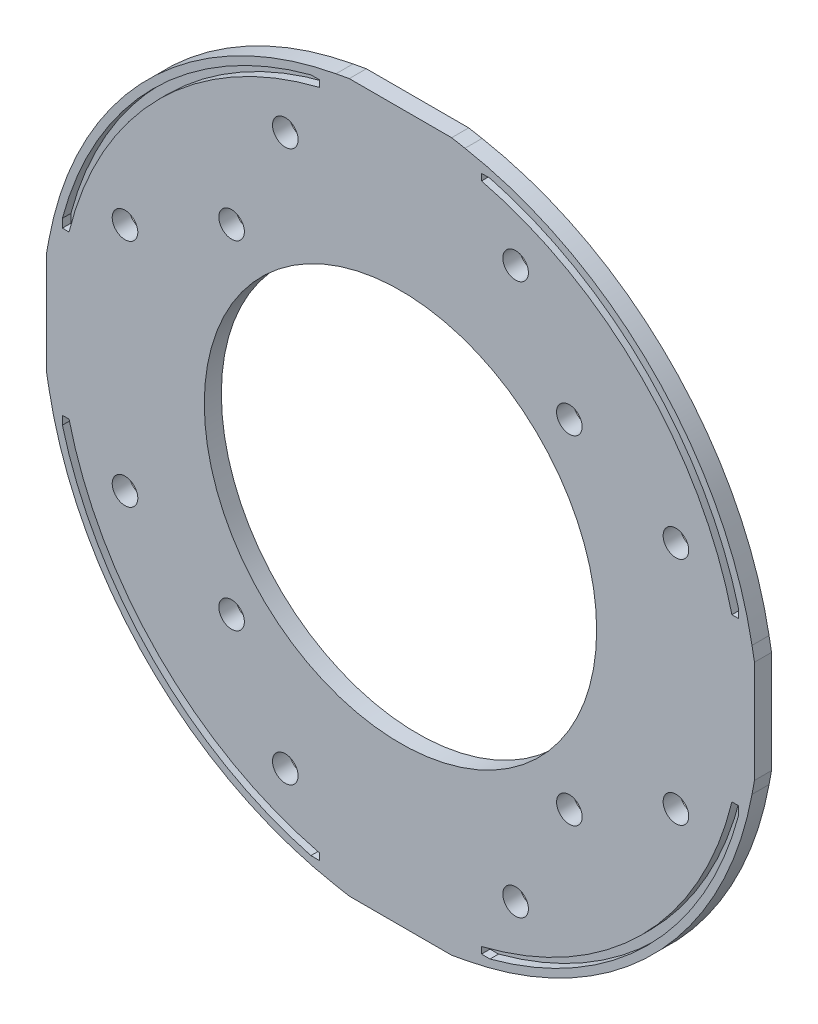
SolidWorks part; units mm, degrees
ref_plane "Спереди" through (0, 0, 0) normal (0, 0, 1) x (1, 0, 0)
ref_plane "Сверху" through (0, 0, 0) normal (0, 1, 0) x (1, 0, 0)
ref_plane "Справа" through (0, 0, 0) normal (1, 0, 0) x (0, 0, -1)
ref_plane "Плоскость4" through (0, 0, -2) normal (0, 0, 1) x (1, 0, 0)
sketch "Эскиз1" plane through (0, 0, -2) normal (0, 0, 1) x (1, 0, 0)
  line L0 (41.5, 6) -> (35.9512, 35.9512)
  line L1 (35.9512, 35.9512) -> (6, 41.5)
  line L2 (6, 41.5) -> (-6, 41.5)
  line L3 (-6, 41.5) -> (-35.9512, 35.9512)
  line L4 (-35.9512, 35.9512) -> (-41.5, 6)
  line L5 (-41.5, 6) -> (-41.5, -6)
  line L6 (-41.5, -6) -> (-35.9512, -35.9512)
  line L7 (-35.9512, -35.9512) -> (-6, -41.5)
  line L8 (-6, -41.5) -> (6, -41.5)
  line L9 (6, -41.5) -> (35.9512, -35.9512)
  line L10 (35.9512, -35.9512) -> (41.5, -6)
  line L11 (41.5, -6) -> (41.5, 6)
extrude "Бобышка-Вытянуть1" add sketch "Эскиз1" against normal blind 2
sketch "Эскиз2" plane through (0, 0, -2) normal (0, 0, 1) x (1, 0, 0)
  line L0 (9.5, -39.6327) -> (10.5, -39.6327)
  line L1 (39.6327, -10.5) -> (39.6327, -9.5)
  line L2 (39.6327, -9.5) -> (38.8555, -9.5)
  line L3 (9.5, -38.8555) -> (9.5, -39.6327)
  arc A0 (10.5, -39.6327) -> (39.6327, -10.5) centre (0, 0) ccw
  arc A1 (38.8555, -9.5) -> (9.5, -38.8555) centre (0, 0) cw
extrude "Вырез-Вытянуть1" cut sketch "Эскиз2" against normal blind 1
sketch "Эскиз3" plane through (0, 0, -2) normal (0, 0, 1) x (1, 0, 0)
  line L0 (-39.6327, -9.5) -> (-39.6327, -10.5)
  line L1 (-10.5, -39.6327) -> (-9.5, -39.6327)
  line L2 (-9.5, -39.6327) -> (-9.5, -38.8555)
  line L3 (-38.8555, -9.5) -> (-39.6327, -9.5)
  arc A0 (-39.6327, -10.5) -> (-10.5, -39.6327) centre (0, 0) ccw
  arc A1 (-9.5, -38.8555) -> (-38.8555, -9.5) centre (0, 0) cw
extrude "Вырез-Вытянуть2" cut sketch "Эскиз3" against normal blind 1
sketch "Эскиз4" plane through (0, 0, -2) normal (0, 0, 1) x (1, 0, 0)
  line L0 (39.6327, 9.5) -> (39.6327, 10.5)
  line L1 (10.5, 39.6327) -> (9.5, 39.6327)
  line L2 (9.5, 39.6327) -> (9.5, 38.8555)
  line L3 (38.8555, 9.5) -> (39.6327, 9.5)
  arc A0 (39.6327, 10.5) -> (10.5, 39.6327) centre (0, 0) ccw
  arc A1 (9.5, 38.8555) -> (38.8555, 9.5) centre (0, 0) cw
extrude "Вырез-Вытянуть3" cut sketch "Эскиз4" against normal blind 1
sketch "Эскиз5" plane through (0, 0, -2) normal (0, 0, 1) x (1, 0, 0)
  line L0 (-9.5, 39.6327) -> (-10.5, 39.6327)
  line L1 (-39.6327, 10.5) -> (-39.6327, 9.5)
  line L2 (-39.6327, 9.5) -> (-38.8555, 9.5)
  line L3 (-9.5, 38.8555) -> (-9.5, 39.6327)
  arc A0 (-10.5, 39.6327) -> (-39.6327, 10.5) centre (0, 0) ccw
  arc A1 (-38.8555, 9.5) -> (-9.5, 38.8555) centre (0, 0) cw
extrude "Вырез-Вытянуть4" cut sketch "Эскиз5" against normal blind 1
hole_wizard "Диаметр отверстия Ø3.0 (3)1" positions "Эскиз7" profile "Эскиз6" hole size "Ø3.0" standard "Ansi Metric"
sketch "Эскиз7" plane through (0, 0, -2) normal (0, 0, 1) x (1, 0, 0)
  point P0 (32.2916, -13.5)
  point P1 (32.2916, 13.5)
  point P2 (19.799, 19.799)
  point P3 (19.799, -19.799)
  point P4 (13.5, -32.2916)
  point P5 (-13.5, -32.2916)
  point P6 (-19.799, -19.799)
  point P7 (-19.799, 19.799)
  point P8 (-13.5, 32.2916)
  point P9 (13.5, 32.2916)
  point P10 (-32.2916, 13.5)
  point P11 (-32.2916, -13.5)
sketch "Эскиз6" plane through (32.2916, -13.5, -2) normal (1, 0, 0) x (0, -1, 0)
  line L0 (0, 0) -> (0, 2)
  line L1 (0, 2) -> (1.5, 2)
  line L2 (1.5, 2) -> (1.5, 0)
  line L5 (1.5, 0) -> (0, 0)
  line L11 (0, -6.35) -> (0, 107.95) construction
  dimension "Диаметр сквозного отверстия" = 3
  dimension "Глубина сквозного отверстия" = 2
hole_wizard "Отверстие с зазором M421" positions "Эскиз9" profile "Эскиз8" hole size "M42" standard "Ansi Metric"
sketch "Эскиз9" plane through (0, 0, -2) normal (0, 0, 1) x (1, 0, 0)
  point P0 (0, 0)
sketch "Эскиз8" plane through (0, 0, -2) normal (1, 0, 0) x (0, -1, 0)
  line L0 (0, 0) -> (0, 2)
  line L1 (0, 2) -> (23, 2)
  line L2 (23, 2) -> (23, 0)
  line L5 (23, 0) -> (0, 0)
  line L11 (0, -6.35) -> (0, 107.95) construction
  dimension "Диаметр сквозного отверстия" = 46
  dimension "Глубина сквозного отверстия" = 2
fillet "Скругление1" radius 42 4 edges at (35.9512, 35.9512, -3) (-35.9512, 35.9512, -3) (35.9512, -35.9512, -3) (-35.9512, -35.9512, -3)
